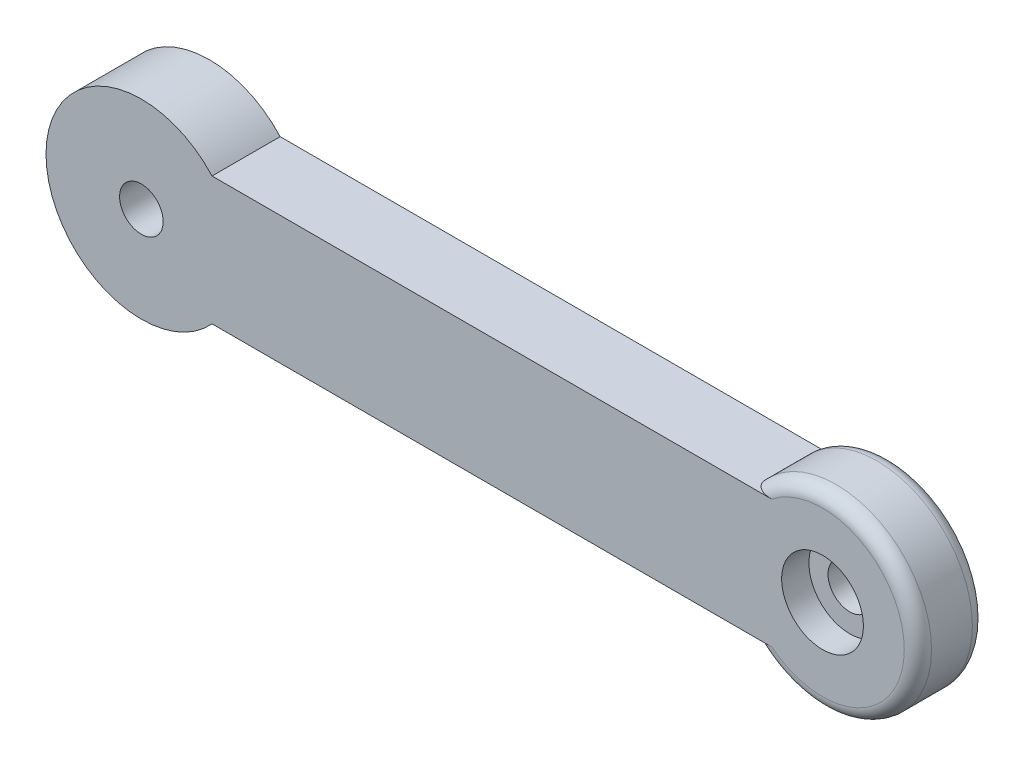
SolidWorks part; units mm, degrees
ref_plane "Front Plane" through (0, 0, 0) normal (0, 0, 1) x (1, 0, 0)
ref_plane "Top Plane" through (0, 0, 0) normal (0, 1, 0) x (1, 0, 0)
ref_plane "Right Plane" through (0, 0, 0) normal (1, 0, 0) x (0, 0, -1)
sketch "Sketch1" plane through (0, 0, 0) normal (0, 0, 1) x (1, 0, 0)
  line L0 (0, 0) -> (50, 0) construction
  line L1 (0, 4.7) -> (50, 4.7)
  line L2 (0, -4.7) -> (50, -4.7)
  circle A0 centre (0, 0) radius 1.6
  circle A1 centre (50, 0) radius 1.6
  circle A2 centre (0, 0) radius 4.7
  circle A3 centre (50, 0) radius 4.7
  dimension "D2" = 9.4
  dimension "D1" = 50
extrude "Boss-Extrude1" add sketch "Sketch1" along normal blind 5
sketch "Sketch2" plane through (0, 0, 5) normal (0, 0, 1) x (1, 0, 0)
  circle A0 centre (50, 0) radius 3
extrude "Cut-Extrude1" cut sketch "Sketch2" against normal blind 2
sketch "Sketch3" plane through (0, 0, 5) normal (0, 0, 1) x (1, 0, 0)
  circle A0 centre (50, 0) radius 4.7
  circle A1 centre (50, 0) radius 7
  circle A2 centre (0, 0) radius 4.7
  circle A3 centre (0, 0) radius 7
extrude "Boss-Extrude2" add sketch "Sketch3" against normal blind 5
fillet "Fillet1" radius 1 2 edges at (57, 0, 5) (57, 0, 0)
